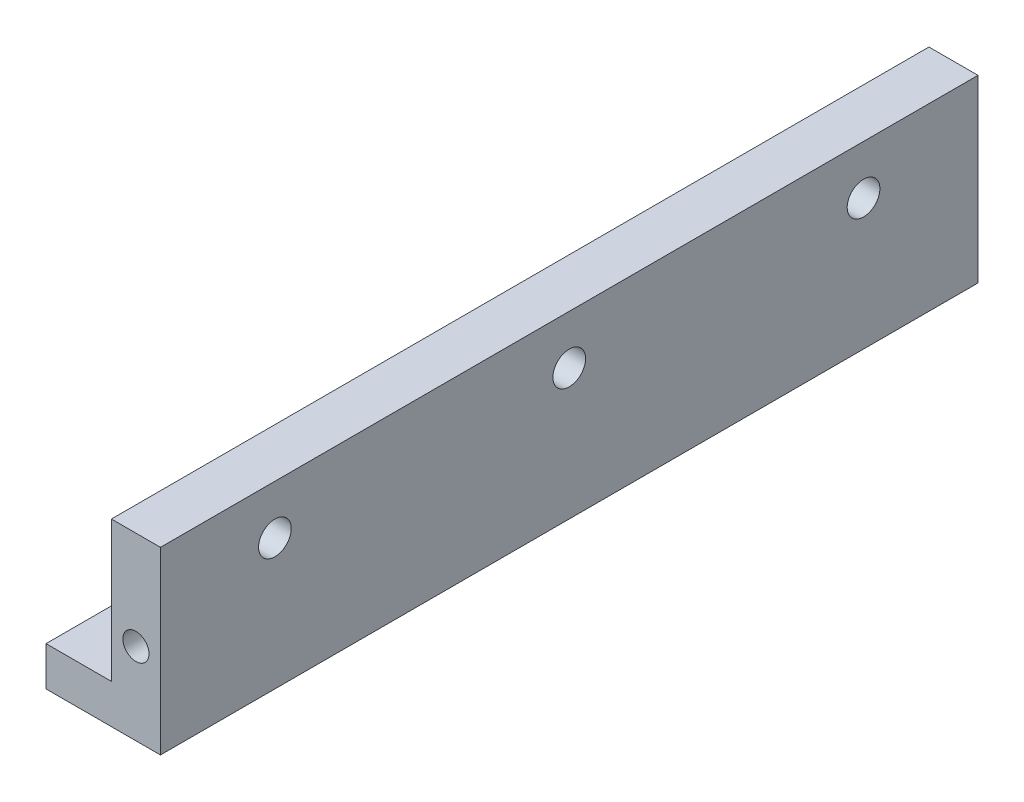
SolidWorks part; units mm, degrees
ref_plane "前基準面" through (0, 0, 0) normal (0, 0, 1) x (1, 0, 0)
ref_plane "上基準面" through (0, 0, 0) normal (0, 1, 0) x (1, 0, 0)
ref_plane "右基準面" through (0, 0, 0) normal (1, 0, 0) x (0, 0, -1)
sketch "草圖1" plane through (0, 0, 0) normal (0, 0, 1) x (1, 0, 0)
  line L0 (-5.0196, 208.8052) -> (-5.0196, 165.8052)
  line L1 (-5.0196, 180.2855) -> (-5.0196, 240.2855) construction
  line L2 (-5.0196, 165.8052) -> (-25.0196, 165.8052)
  line L3 (-25.0196, 165.8052) -> (-25.0196, 153.8052)
  line L4 (-25.0196, 153.8052) -> (9.9804, 153.8052)
  line L5 (9.9804, 153.8052) -> (9.9804, 208.8052)
  line L6 (9.9804, 208.8052) -> (-5.0196, 208.8052)
  circle A0 centre (2.4804, 178.8052) radius 4
  dimension "D5" = 8
  dimension "D7" = 30
  dimension "D1" = 35
  dimension "D2" = 12
  dimension "D3" = 55
  dimension "D4" = 15
  dimension "D6" = 7.5
extrude "填料-伸長1" add sketch "草圖1" against normal up to surface (250 mm away)
sketch "草圖2" plane through (9.9804, 0, 0) normal (1, 0, 0) x (0, 0, -1)
  line L0 (0, 153.8052) -> (0, 208.8052) construction
  line L1 (250, 208.8052) -> (0, 208.8052) construction
  circle A0 centre (35, 193.8052) radius 5
  circle A1 centre (125, 193.8052) radius 5
  circle A2 centre (215, 193.8052) radius 5
  dimension "D1" = 10
  dimension "D2" = 10
  dimension "D3" = 10
  dimension "D7" = 15
  dimension "D4" = 90
  dimension "D5" = 90
  dimension "D6" = 35
extrude "除料-伸長1" cut sketch "草圖2" against normal up to next and the other way through all
